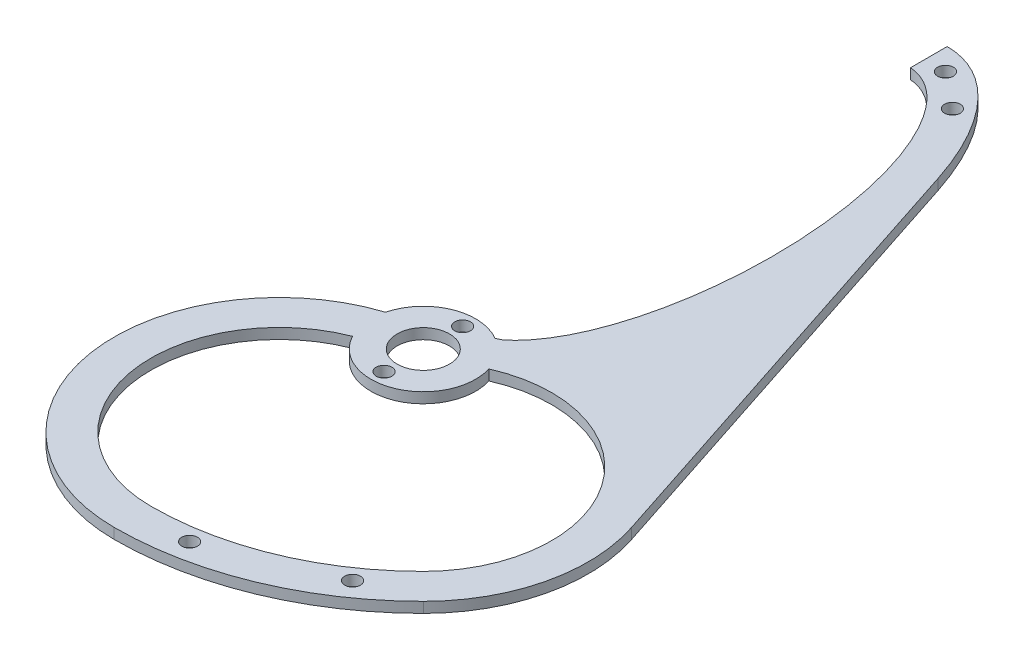
SolidWorks part; units mm, degrees
ref_plane "Спереди" through (0, 0, 0) normal (0, 0, 1) x (1, 0, 0)
ref_plane "Сверху" through (0, 0, 0) normal (0, 1, 0) x (1, 0, 0)
ref_plane "Справа" through (0, 0, 0) normal (1, 0, 0) x (0, 0, -1)
sketch "Эскиз1" plane through (0, 0, 0) normal (0, 1, 0) x (1, 0, 0)
  line L0 (0, 0) -> (0, -55) construction
  line L1 (9.5506, -54.1644) -> (0, 0) construction
  line L2 (0, 0) -> (35.7004, -86.1885) construction
  line L3 (20.9205, 77.3689) -> (49.3845, -9.6526)
  line L4 (0, 0) -> (0, 100) construction
  line L5 (0, 93) -> (0, 100)
  line L7 (0, 0) -> (38.8909, -38.8909) construction
  arc A0 (0, -59) -> (41.7193, -41.7193) centre (0, 0) ccw
  arc A1 (0, -52) -> (36.7696, -36.7696) centre (0, 0) ccw
  arc A2 (0, -55) -> (55, 0) centre (0, 0) ccw construction
  circle A3 centre (9.5506, -54.1644) radius 1.5
  circle A4 centre (31.5467, -45.0534) radius 1.5
  circle A5 centre (19.4454, -19.4454) radius 24.5 construction
  circle A6 centre (0, 0) radius 5
  circle A7 centre (19.4454, -19.4454) radius 31.5 construction
  arc A8 (41.7193, -41.7193) -> (49.3845, -9.6526) centre (19.4454, -19.4454) ccw
  arc A9 (-2.9671, -9.5497) -> (9.5497, 2.9671) centre (0, 0) ccw
  arc A10 (36.7696, -36.7696) -> (9.5497, 2.9671) centre (19.4454, -19.4454) ccw
  arc A11 (6.0324, 9.0562) -> (5.103, 8.6) centre (19.4454, -19.4454) ccw
  arc A12 (5.103, 8.6) -> (-9.6895, 2.4727) centre (0, 0) ccw
  circle A13 centre (0, 0) radius 7.5 construction
  circle A14 centre (0, -7.5) radius 1.5
  circle A15 centre (0, 7.5) radius 1.5
  circle A16 centre (0, -27.5) radius 24.5 construction
  circle A17 centre (0, -27.5) radius 31.5 construction
  arc A18 (0, -52) -> (-8.8507, -4.6545) centre (0, -27.5) cw
  arc A19 (0, -59) -> (-9.6895, 2.4727) centre (0, -27.5) cw
  arc A20 (-8.8507, -4.6545) -> (-2.9671, -9.5497) centre (0, 0) ccw
  ellipse E2 centre (0, 50) end of major axis (-0.6457, 93.0179) minor radius 18.0072 (6.0324, 9.0562) -> (0, 93) ccw
  ellipse E3 centre (0, 50) end of major axis (-0.004, 100) minor radius 25 (20.9205, 77.3689) -> (0, 100) ccw
  dimension "D1" = 59
  dimension "D2" = 55
  dimension "D3" = 52
  dimension "D4" = 3
  dimension "D7" = 50
  dimension "D8" = 10
  dimension "D9" = 10
  dimension "D10" = 7
  dimension "D11" = 7
  dimension "D12" = 25
  dimension "D5" = 10
  dimension "D6" = 22.5
extrude "Бобышка-Вытянуть1" add sketch "Эскиз1" along normal blind 2
sketch "Эскиз2" plane through (0, 0, 0) normal (0, -1, 0) x (1, 0, 0)
  line L0 (0, 0) -> (0, -100) construction
  line L1 (0, -50) -> (4.795, -104.807) construction
  line L2 (0, -50) -> (14.3957, -103.7253) construction
  circle A0 centre (3.9973, -95.6893) radius 1.5
  circle A1 centre (10.7802, -90.2324) radius 1.5
  ellipse E0 centre (0, -50) end of major axis (0.004, 0) minor radius 25 (0, -100) -> (20.9205, -77.3689) ccw construction
  ellipse E1 centre (0, -50) end of major axis (0, -3.5) minor radius 21.5 construction
  dimension "D1" = 5
  dimension "D2" = 15
extrude "Вырез-Вытянуть1" cut sketch "Эскиз2" against normal through all
